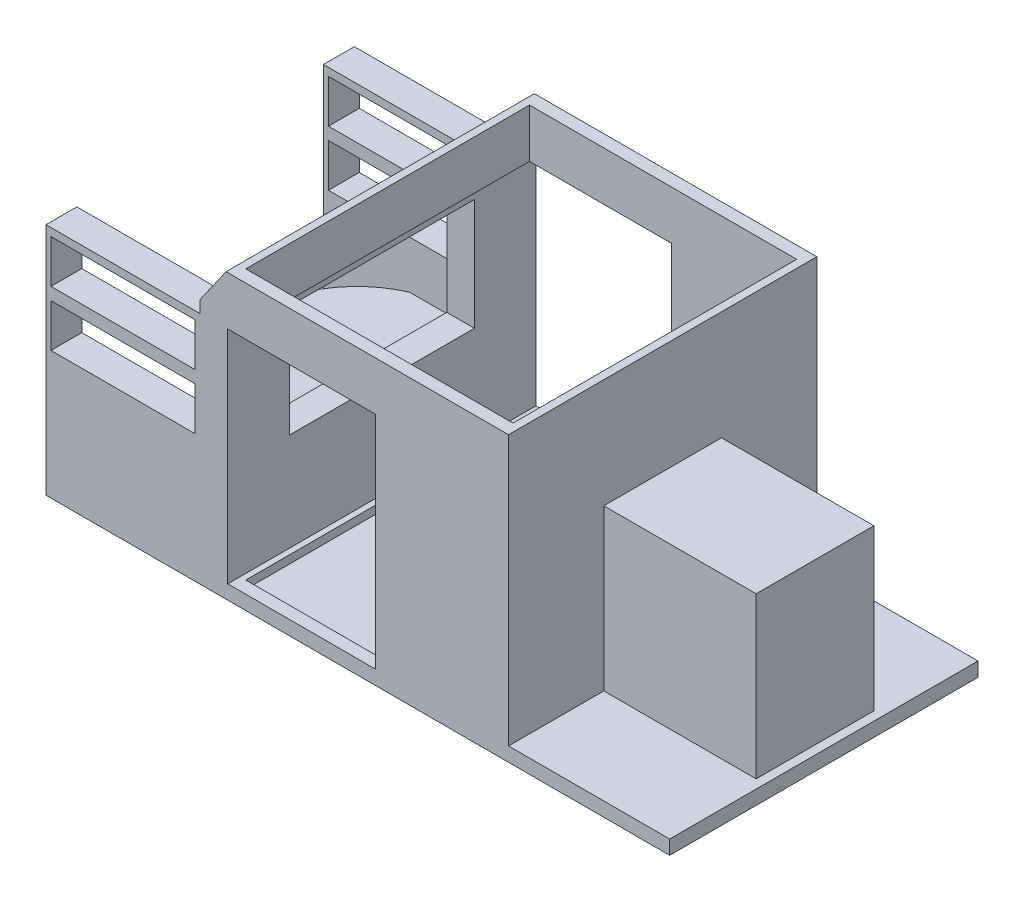
SolidWorks part; units mm, degrees
material "Acero al carbono no aleado"
ref_plane "Alzado" through (0, 0, 0) normal (0, 0, 1) x (1, 0, 0)
ref_plane "Planta" through (0, 0, 0) normal (0, 1, 0) x (1, 0, 0)
ref_plane "Vista lateral" through (0, 0, 0) normal (1, 0, 0) x (0, 0, -1)
sketch "Croquis1" plane through (0, 0, 0) normal (0, 1, 0) x (1, 0, 0)
  line L0 (-1875, 1000) -> (-625, 1000)
  line L1 (-1875, 1250) -> (1875, 1250)
  line L2 (-1875, 1250) -> (-1875, 1000)
  line L3 (-1875, -1250) -> (1875, -1250)
  line L4 (1875, 1250) -> (1875, -1250)
  line L5 (-1875, 1250) -> (1875, -1250) construction
  line L6 (-1875, -1250) -> (1875, 1250) construction
  line L8 (-1875, -1000) -> (-625, -1000)
  line L10 (-625, 1000) -> (-625, -1000)
  line L11 (-1875, -1000) -> (-1875, -1250)
  point P0 (0, 0)
  dimension "D1" = 2500
  dimension "D2" = 3750
  dimension "D3" = 250
  dimension "D4" = 1250
  dimension "D5" = 250
  dimension "D6" = 1250
extrude "Saliente-Extruir1" add sketch "Croquis1" along normal blind 2300
sketch "Croquis2" plane through (0, 0, 1250) normal (0, 0, 1) x (1, 0, 0)
  line L0 (-1875, 2300) -> (-625, 2300)
  line L1 (-625, 2300) -> (-625, 1900)
  line L2 (-625, 2300) -> (-625, 0) construction
  line L3 (-625, 1900) -> (-1875, 1900)
  line L4 (-1875, 2300) -> (-1875, 0) construction
  line L5 (-1875, 1900) -> (-1875, 2300)
  dimension "D1" = 400
extrude "Cortar-Extruir1" cut sketch "Croquis2" along direction (0, 0, 1) on the side against the normal up to vertex (2500 mm away)
sketch "Croquis3" plane through (0, 0, 1250) normal (0, 0, 1) x (1, 0, 0)
  line L0 (-625, 2000) -> (-414.9377, 2300)
  line L1 (-625, 1900) -> (-625, 2300) construction
  line L2 (-625, 2300) -> (1875, 2300) construction
  line L3 (-625, 2000) -> (-625, 2300)
  line L4 (-625, 2300) -> (-414.9377, 2300)
  dimension "D1" = 300
  dimension "D2" = 125
extrude "Cortar-Extruir2" cut sketch "Croquis3" along direction (0, 0, 1) on the side against the normal up to vertex (2500 mm away)
sketch "Croquis4" plane through (0, 2300, 0) normal (0, 1, 0) x (1, 0, 0)
  line L0 (1875, 1250) -> (-414.9377, 1250) construction
  line L1 (-354.9377, -1150) -> (1811.4763, -1150)
  line L2 (-354.9377, -1150) -> (-354.9377, 1150)
  line L3 (-354.9377, 1150) -> (1811.4763, 1150)
  line L4 (1811.4763, -1150) -> (1811.4763, 1150)
  line L5 (-354.9377, -1150) -> (1811.4763, 1150) construction
  line L6 (-354.9377, 1150) -> (1811.4763, -1150) construction
  line L8 (-414.9377, 1250) -> (-414.9377, -1250) construction
  point P0 (728.2693, 0)
  dimension "D1" = 2300
  dimension "D2" = 100
  dimension "D3" = 60
extrude "Cortar-Extruir3" cut sketch "Croquis4" against normal blind 2250
sketch "Croquis5" plane through (0, 0, 1250) normal (0, 0, 1) x (1, 0, 0)
  line L0 (-1875, 1900) -> (-1875, 0) construction
  line L1 (-1835, 1836.7195) -> (-665, 1836.7195)
  line L2 (-1835, 1836.7195) -> (-1835, 1486.7195)
  line L3 (-1835, 1486.7195) -> (-665, 1486.7195)
  line L4 (-665, 1836.7195) -> (-665, 1486.7195)
  dimension "D1" = 350
  dimension "D2" = 1170
  dimension "D3" = 40
extrude "Cortar-Extruir4" cut sketch "Croquis5" against normal up to vertex (2500 mm away) up to point (-1875, 1900, -1250)
pattern_linear "MatrizL1" count 2 spacing 450 along (0, -1, 0) of "Cortar-Extruir4"
sketch "Croquis7" plane through (0, 0, 1250) normal (0, 0, 1) x (1, 0, 0)
  line L1 (-401.4917, 1904.7174) -> (798.5083, 1904.7174)
  line L2 (-401.4917, 1904.7174) -> (-401.4917, 114.7174)
  line L3 (-401.4917, 114.7174) -> (798.5083, 114.7174)
  line L4 (798.5083, 1904.7174) -> (798.5083, 114.7174)
  dimension "D1" = 1790
  dimension "D2" = 1200
extrude "Cortar-Extruir5" cut sketch "Croquis7" against normal up to surface (2500 mm away)
sketch "Croquis8" plane through (0, 0, 0) normal (0, 1, 0) x (1, 0, 0)
  line L1 (1875, 1250) -> (3181.871, 1250)
  line L2 (1875, 1250) -> (1875, -1250)
  line L3 (1875, -1250) -> (3181.871, -1250)
  line L4 (3181.871, 1250) -> (3181.871, -1250)
extrude "Saliente-Extruir2" add sketch "Croquis8" along normal up to surface (114.7174 mm away) up to face at (210.1468, 114.7174, 0)
sketch "Croquis9" plane through (0, 114.7174, 0) normal (0, 1, 0) x (1, 0, 0)
  line L1 (1875, -477.2701) -> (3110.3334, -477.2701)
  line L2 (1875, -477.2701) -> (1875, 477.2701)
  line L3 (1875, 477.2701) -> (3110.3334, 477.2701)
  line L4 (3110.3334, -477.2701) -> (3110.3334, 477.2701)
  line L5 (1875, -477.2701) -> (3110.3334, 477.2701) construction
  line L6 (1875, 477.2701) -> (3110.3334, -477.2701) construction
  point P0 (2492.6667, 0)
extrude "Saliente-Extruir3" add sketch "Croquis9" along normal blind 1300
ref_plane "Plano1" through (0, 850, 0) normal (0, 1, 0) x (1, 0, 0)
sketch "Croquis10" plane through (0, 850, 0) normal (0, 1, 0) x (1, 0, 0)
  line L1 (-625, 750) -> (-925, 750)
  line L2 (-625, 1250) -> (-625, -1250) construction
  line L3 (-625, -750) -> (-925, -750)
  line L4 (-625, 1000) -> (-1875, 1000) construction
  line L5 (-1875, -1000) -> (-625, -1000) construction
  line L10 (-625, -1250) -> (-414.9377, -1250)
  line L11 (-414.9377, -1250) -> (-414.9377, 1250)
  line L12 (-414.9377, 1250) -> (-625, 1250)
  line L13 (-625, 1250) -> (-625, -1250)
  line L17 (-625, 750) -> (-625, -750)
  arc A0 (-925, 750) -> (-925, -750) centre (-603.766, 0) ccw
  dimension "D1" = 250
  dimension "D2" = 300
  dimension "D4" = 250
  dimension "D3" = 0
extrude "Saliente-Extruir4" add sketch "Croquis10" along normal blind 50
sketch "Croquis11" plane through (-625, 0, 0) normal (-1, 0, 0) x (0, 0, 1)
  line L1 (-750, 909.2685) -> (750, 909.2685)
  line L2 (-750, 909.2685) -> (-750, 1813.8085)
  line L3 (-750, 1813.8085) -> (750, 1813.8085)
  line L4 (750, 909.2685) -> (750, 1813.8085)
  line L5 (-750, 909.2685) -> (750, 1813.8085) construction
  line L6 (-750, 1813.8085) -> (750, 909.2685) construction
  line L7 (750, 900) -> (750, 850) construction
  line L8 (-750, 900) -> (-750, 850) construction
  point P0 (0, 1361.5385)
  dimension "D1" = 1500
  dimension "D2" = 904.54
extrude "Cortar-Extruir6" cut sketch "Croquis11" against normal up to surface (223.5083 mm away) up to face at (-401.4917, 1009.7174, 0)
